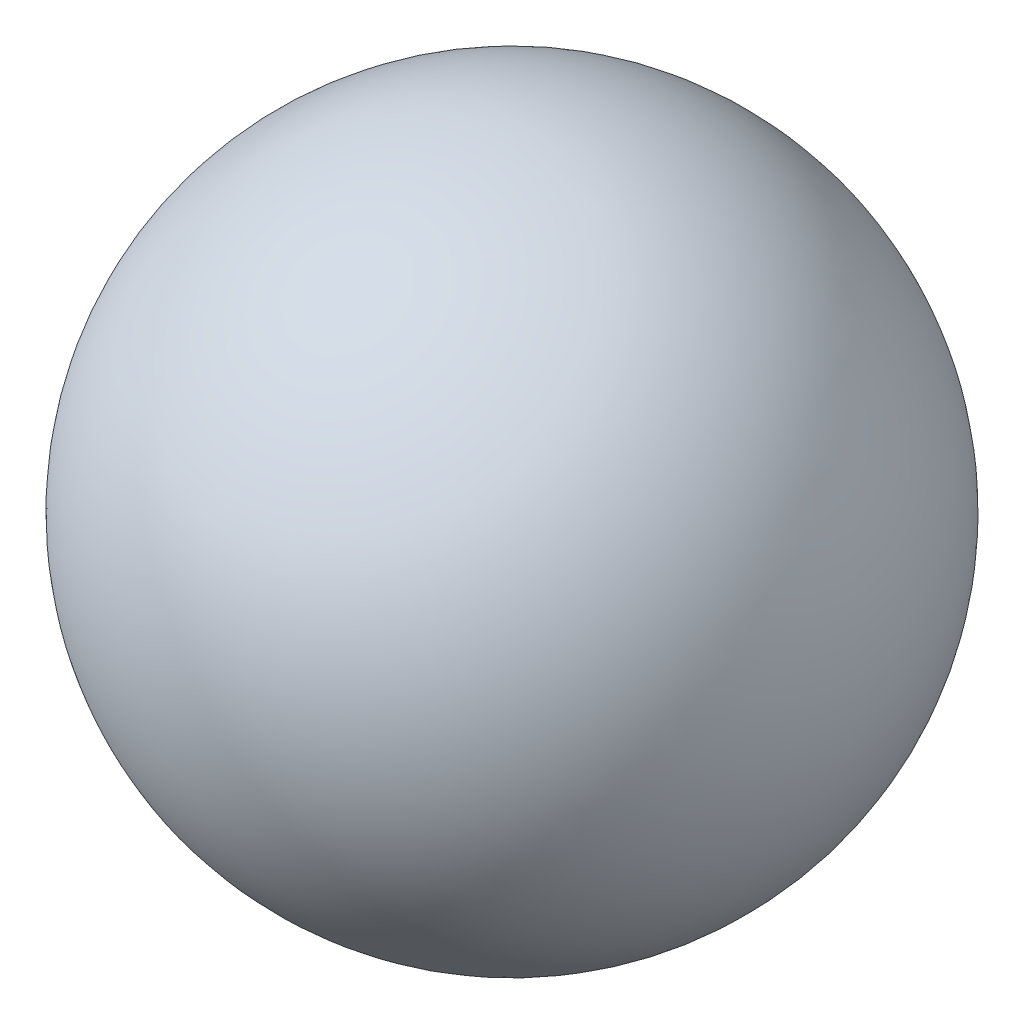
SolidWorks part; units mm, degrees
ref_plane "Front Plane" through (0, 0, 0) normal (0, 0, 1) x (1, 0, 0)
ref_plane "Top Plane" through (0, 0, 0) normal (0, 1, 0) x (1, 0, 0)
ref_plane "Right Plane" through (0, 0, 0) normal (1, 0, 0) x (0, 0, -1)
sketch "Sketch1" plane through (0, 0, 0) normal (0, 1, 0) x (1, 0, 0)
  line L0 (0, 34.25) -> (0, -34.25)
  arc A0 (0, 34.25) -> (0, -34.25) centre (0, 0) cw
  point P6 (0, 0)
  dimension "D1" = 34.25
revolve "Revolve1" add sketch "Sketch1" angle 360 about L0
ref_point "Point2"
